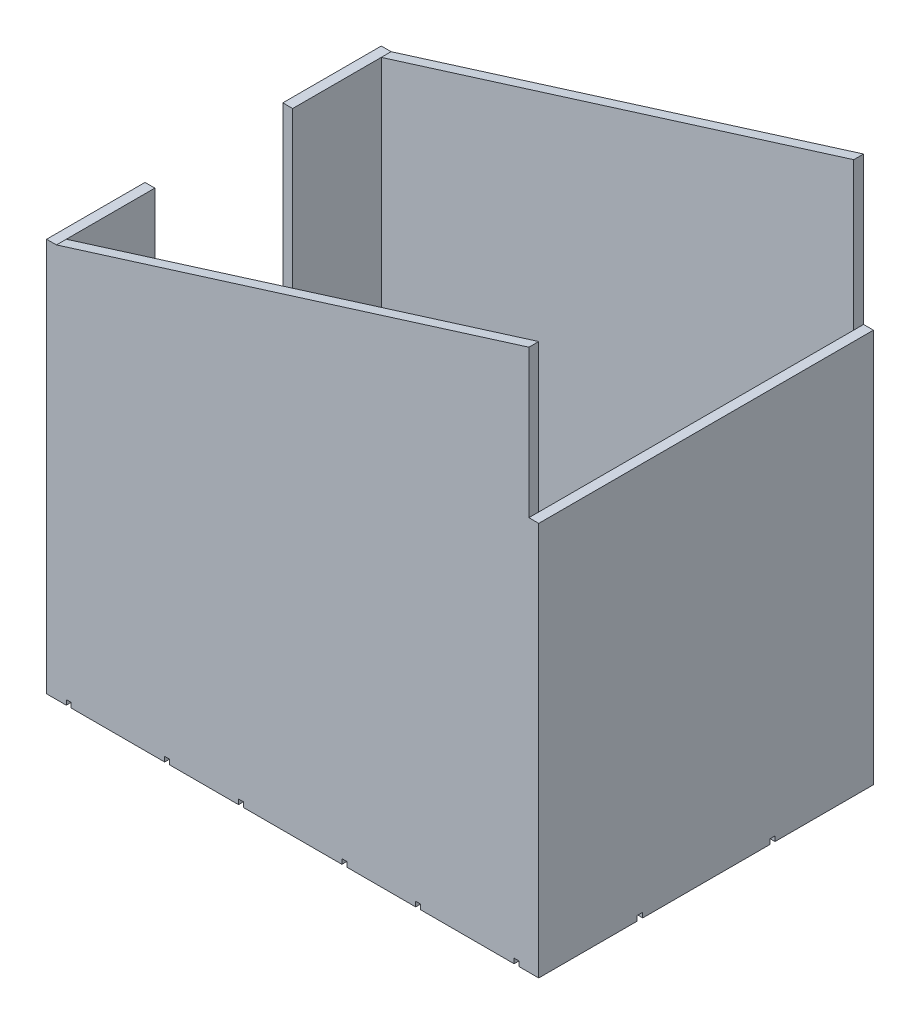
SolidWorks part; units mm, degrees
ref_plane "前视基准面" through (0, 0, 0) normal (0, 0, 1) x (1, 0, 0)
ref_plane "上视基准面" through (0, 0, 0) normal (0, 1, 0) x (1, 0, 0)
ref_plane "右视基准面" through (0, 0, 0) normal (1, 0, 0) x (0, 0, -1)
other "Configuration Table"
sketch "草图1" plane through (0, 0, 0) normal (0, 1, 0) x (1, 0, 0)
  line L0 (0, 0) -> (0, -20)
  line L1 (0, 0) -> (100, 0)
  line L3 (0, -68) -> (100, -68)
  line L4 (100, 0) -> (100, -68)
  line L5 (0, -20) -> (60, -20)
  line L7 (60, -48) -> (0, -48)
  line L8 (0, -48) -> (0, -68)
  line L9 (40, -35) -> (-49960, -35) construction
  line L10 (60, -21.2085) -> (60, -50021.2085) construction
  arc A0 (60, -20) -> (60, -48) centre (60, -34) cw
  dimension "D1" = 68
  dimension "D2" = 100
  dimension "D3" = 20
  dimension "D4" = 20
  dimension "D5" = 60
extrude "凸台-拉伸1" add sketch "草图1" along normal blind 3
sketch "草图2" plane through (0, 3, 0) normal (0, 1, 0) x (1, 0, 0)
  line L0 (2, -20) -> (0, -20)
  line L1 (0, -20) -> (60, -20) construction
  line L2 (0, 0) -> (0, -20) construction
  line L3 (0, -20) -> (0, 0)
  line L4 (0, 0) -> (100, 0)
  line L5 (100, 0) -> (0, 0) construction
  line L6 (100, -68) -> (100, 0) construction
  line L7 (100, 0) -> (100, -68)
  line L8 (100, -68) -> (0, -68)
  line L9 (0, -68) -> (0, -48)
  line L10 (0, -48) -> (0, -68) construction
  line L11 (0, -48) -> (2, -48)
  line L12 (60, -48) -> (0, -48) construction
  line L13 (2, -48) -> (2, -66)
  line L14 (2, -66) -> (98, -66)
  line L15 (98, -66) -> (98, -2)
  line L16 (98, -2) -> (2, -2)
  line L17 (2, -2) -> (2, -20)
  dimension "D1" = 2
  dimension "D2" = 2
  dimension "D3" = 2
  dimension "D4" = 2
extrude "凸台-拉伸2" add sketch "草图2" along normal blind 77
sketch "草图3" plane through (0, 80, 0) normal (0, 1, 0) x (1, 0, 0)
  line L0 (2, -2) -> (2, 0)
  line L1 (100, 0) -> (0, 0) construction
  line L5 (0, -68) -> (100, -68) construction
  line L6 (2, -68) -> (2, -66)
  line L7 (2, -66) -> (98, -66)
  line L9 (98, -2) -> (98, -66) construction
  line L10 (98, -2) -> (98, -66) construction
  line L11 (98, -2) -> (2, -2)
  line L12 (2, 0) -> (98, 0)
  line L13 (98, 0) -> (98, -2)
  line L14 (98, -66) -> (98, -68)
  line L15 (98, -68) -> (2, -68)
extrude "凸台-拉伸3" add sketch "草图3" along normal blind 30
sketch "草图6" plane through (0, 0, 68) normal (0, 0, 1) x (1, 0, 0)
  line L0 (2, 110) -> (2, 80)
  line L1 (2, 80) -> (98, 110)
  line L2 (98, 110) -> (2, 110)
extrude "切除-拉伸1" cut sketch "草图6" against normal through all
sketch "草图7" plane through (0, 3, 0) normal (0, 1, 0) x (1, 0, 0)
  line L0 (2, -20) -> (2, -2)
  line L1 (2, -2) -> (98, -2) construction
  line L2 (2, -20) -> (2, -2) construction
  line L3 (2, -2) -> (98, -2)
  line L4 (98, -2) -> (98, -66)
  line L5 (98, -66) -> (2, -66)
  line L6 (2, -66) -> (2, -48)
  line L7 (2, -48) -> (60, -48)
  line L8 (60, -48) -> (2, -48) construction
  line L9 (2, -20) -> (60, -20)
  line L10 (2, -20) -> (60, -20) construction
  arc A0 (60, -48) -> (60, -20) centre (60, -34) ccw construction
  arc A1 (60, -20) -> (60, -48) centre (60, -34) cw
  line M1 (2, -2) -> (2, -20)
  line M2 (2, -20) -> (60, -20)
  arc M3 (60, -20) -> (60, -48) centre (60, -34) cw
  line M4 (60, -48) -> (2, -48)
  line M5 (2, -48) -> (2, -66)
  line M6 (2, -66) -> (98, -66)
  line M7 (98, -66) -> (98, -2)
  line M8 (98, -2) -> (2, -2)
extrude "凸台-拉伸4" add sketch "草图7" along normal blind 3 contours M8 M1 M2 M3 M4 M5 M6 M7
sketch "草图8" plane through (0, 6, 0) normal (0, 1, 0) x (1, 0, 0)
  line L0 (60, -34) -> (50060, -34) construction
  line L1 (23.1673, 1) -> (50023.1673, 1) construction
  line L2 (16.0946, -69) -> (50016.0946, -69) construction
  line L3 (-16.6734, -59) -> (49983.3266, -59) construction
  line L4 (-8.5361, -9) -> (49991.4639, -9) construction
  line L5 (15, -34) -> (15, -50034) construction
  line L6 (50, -34) -> (50, -50034) construction
  line L7 (85, -34) -> (85, -50034) construction
  line L10 (2, 0) -> (98, 0) construction
  circle A0 centre (15, -9) radius 2
  circle A1 centre (50, -9) radius 2
  circle A2 centre (85, -9) radius 2
  circle A3 centre (15, -59) radius 2
  circle A4 centre (50, -59) radius 2
  circle A5 centre (85, -59) radius 2
  point P21 (50, 0)
  dimension "D7" = 4
  dimension "D8" = 4
  dimension "D9" = 4
  dimension "D10" = 4
  dimension "D11" = 4
  dimension "D12" = 4
  dimension "D1" = 35
  dimension "D2" = 35
  dimension "D3" = 10
  dimension "D4" = 10
  dimension "D5" = 35
  dimension "D6" = 35
extrude "切除-拉伸2" cut sketch "草图8" against normal blind 3
sketch "草图9" plane through (0, 6, 0) normal (0, 1, 0) x (1, 0, 0)
  circle A0 centre (15, -9) radius 1.15
  circle A1 centre (50, -9) radius 1.15
  circle A2 centre (85, -9) radius 1.15
  circle A3 centre (85, -59) radius 1.15
  circle A4 centre (50, -59) radius 1.15
  circle A5 centre (15, -59) radius 1.15
  dimension "D1" = 2.3
  dimension "D2" = 2.3
  dimension "D3" = 2.3
  dimension "D4" = 2.3
  dimension "D5" = 2.3
  dimension "D6" = 2.3
extrude "切除-拉伸3" cut sketch "草图9" against normal blind 23
sketch "草图10" plane through (0, 0, 0) normal (0, -1, 0) x (1, 0, 0)
  line L0 (0, 68) -> (100, 68) construction
  line L1 (24, 68) -> (25, 68)
  line L2 (24, 68) -> (24, 0)
  line L3 (24, 0) -> (25, 0)
  line L4 (25, 68) -> (25, 0)
  line L5 (100, 0) -> (0, 0) construction
  line L6 (50, 59) -> (50, -49941) construction
  line L7 (39, 68) -> (40, 68)
  line L8 (39, 68) -> (39, 0)
  line L9 (39, 0) -> (40, 0)
  line L10 (40, 68) -> (40, 0)
  line L11 (60, 68) -> (61, 68)
  line L12 (60, 68) -> (60, 0)
  line L13 (60, 0) -> (61, 0)
  line L14 (61, 68) -> (61, 0)
  line L15 (75, 68) -> (76, 68)
  line L16 (75, 68) -> (75, 0)
  line L17 (75, 0) -> (76, 0)
  line L18 (76, 68) -> (76, 0)
  line L19 (95, 68) -> (96, 68)
  line L20 (95, 68) -> (95, 0)
  line L21 (95, 0) -> (96, 0)
  line L22 (96, 68) -> (96, 0)
  line L23 (4, 68) -> (5, 68)
  line L24 (4, 68) -> (4, 0)
  line L25 (4, 0) -> (5, 0)
  line L26 (5, 68) -> (5, 0)
  point P32 (2, 68)
  point P33 (5, 68)
  point P34 (3.1087, 68)
  dimension "D1" = 10
  dimension "D2" = 1
  dimension "D3" = 1
  dimension "D4" = 10
  dimension "D5" = 25
  dimension "D6" = 1
  dimension "D7" = 1
  dimension "D8" = 45
  dimension "D9" = 25
  dimension "D10" = 1
  dimension "D11" = 45
  dimension "D12" = 1
extrude "切除-拉伸4" cut sketch "草图10" against normal blind 1
sketch "草图11" plane through (0, 0, 0) normal (0, -1, 0) x (1, 0, 0)
  line L0 (100, 68) -> (100, 0) construction
  line L1 (0, 48) -> (100, 48)
  line L2 (0, 48) -> (0, 46.8695)
  line L3 (0, 46.8695) -> (100, 46.8695)
  line L4 (100, 48) -> (100, 46.8695)
  line L6 (0, 20) -> (100, 20)
  line L7 (0, 20) -> (0, 21)
  line L8 (0, 21) -> (100, 21)
  line L9 (100, 20) -> (100, 21)
  dimension "D1" = 1
extrude "切除-拉伸5" cut sketch "草图11" against normal blind 1
